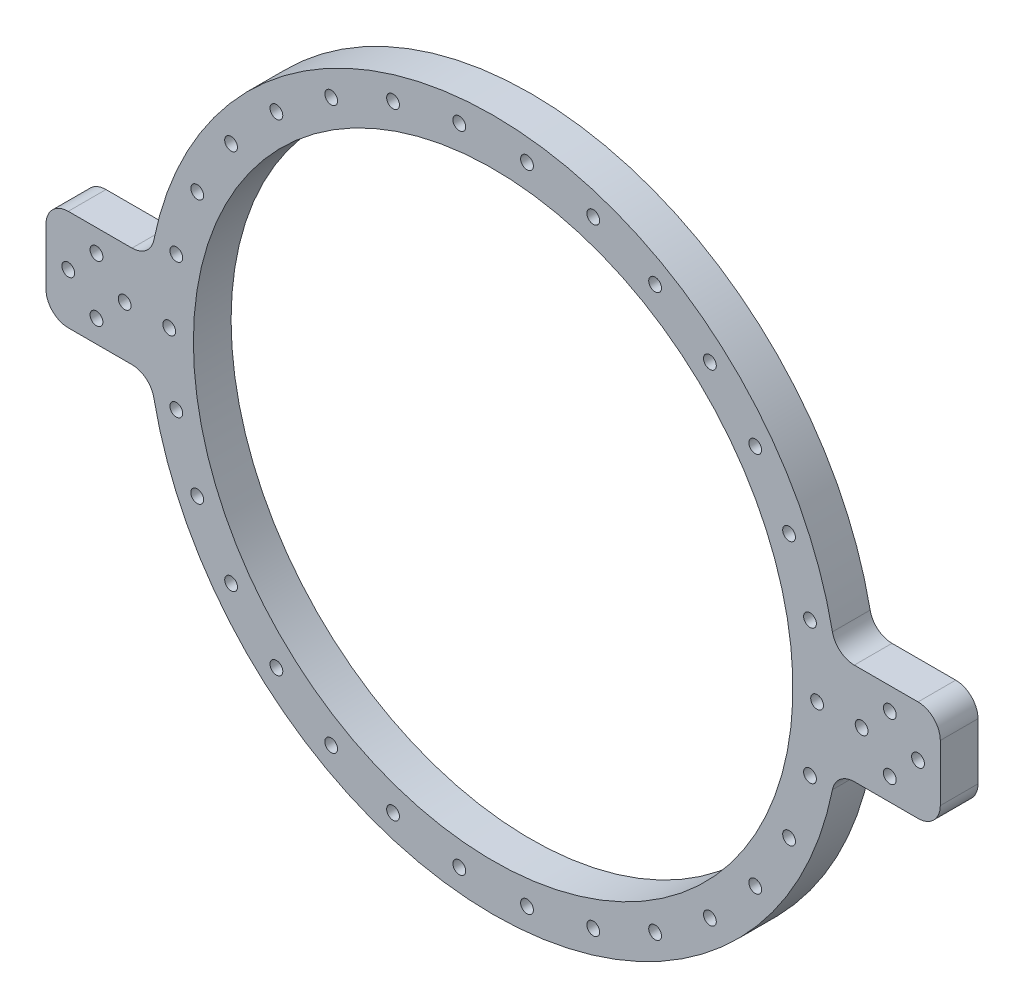
SolidWorks part; units mm, degrees
material "PC High Viscosity"
ref_plane "Front Plane" through (0, 0, 0) normal (0, 0, 1) x (1, 0, 0)
ref_plane "Top Plane" through (0, 0, 0) normal (0, 1, 0) x (1, 0, 0)
ref_plane "Right Plane" through (0, 0, 0) normal (1, 0, 0) x (0, 0, -1)
sketch "Sketch1" plane through (0, 0, 0) normal (0, 0, 1) x (1, 0, 0)
  line L0 (109.1, 0) -> (101.6, 0) construction
  line L1 (109.1, 0) -> (116.6, 0) construction
  line L2 (115.3265, 17) -> (143.1, 17)
  line L3 (150.6, 9.5) -> (150.6, -9.5)
  line L4 (143.1, -17) -> (115.3265, -17)
  line L5 (0, 0) -> (204.7679, 0) construction
  line L6 (0, 0) -> (0, 58.5097) construction
  line L7 (133.6, 9.5) -> (143.1, 0) construction
  line L8 (143.1, 0) -> (133.6, -9.5) construction
  line L9 (133.6, -9.5) -> (124.1, 0) construction
  line L10 (124.1, 0) -> (133.6, 9.5) construction
  line L11 (133.6, 9.5) -> (133.6, 17) construction
  line L12 (124.1, 0) -> (116.6, 0) construction
  line L13 (-115.3265, 17) -> (-143.1, 17)
  line L14 (-150.6, 9.5) -> (-150.6, -9.5)
  line L15 (-143.1, -17) -> (-115.3265, -17)
  circle A0 centre (0, 0) radius 101.6
  arc A1 (115.3265, 17) -> (-115.3265, 17) centre (0, 0) ccw
  circle A2 centre (109.1, 0) radius 2.1527
  circle A4 centre (106.7159, -22.6832) radius 2.1527
  circle A5 centre (99.6678, -44.375) radius 2.1527
  circle A6 centre (88.2638, -64.1274) radius 2.1527
  circle A7 centre (73.0021, -81.0771) radius 2.1527
  circle A8 centre (54.55, -94.4834) radius 2.1527
  circle A9 centre (33.7138, -103.7603) radius 2.1527
  circle A10 centre (11.4041, -108.5023) radius 2.1527
  circle A11 centre (-11.4041, -108.5023) radius 2.1527
  circle A12 centre (-33.7138, -103.7603) radius 2.1527
  circle A13 centre (-54.55, -94.4834) radius 2.1527
  circle A14 centre (-73.0021, -81.0771) radius 2.1527
  circle A15 centre (-88.2638, -64.1274) radius 2.1527
  circle A16 centre (-99.6678, -44.375) radius 2.1527
  circle A17 centre (-106.7159, -22.6832) radius 2.1527
  circle A18 centre (-109.1, 0) radius 2.1527
  circle A19 centre (-106.7159, 22.6832) radius 2.1527
  circle A20 centre (-99.6678, 44.375) radius 2.1527
  circle A21 centre (-88.2638, 64.1274) radius 2.1527
  circle A22 centre (-73.0021, 81.0771) radius 2.1527
  circle A23 centre (-54.55, 94.4834) radius 2.1527
  circle A24 centre (-33.7138, 103.7603) radius 2.1527
  circle A25 centre (-11.4041, 108.5023) radius 2.1526
  circle A26 centre (11.4041, 108.5023) radius 2.1527
  circle A27 centre (33.7138, 103.7603) radius 2.1527
  circle A28 centre (54.55, 94.4834) radius 2.1527
  circle A29 centre (73.0021, 81.0771) radius 2.1527
  circle A30 centre (88.2638, 64.1274) radius 2.1527
  circle A31 centre (99.6678, 44.375) radius 2.1527
  circle A32 centre (106.7159, 22.6832) radius 2.1527
  arc A33 (143.1, 17) -> (150.6, 9.5) centre (143.1, 9.5) cw
  arc A34 (150.6, -9.5) -> (143.1, -17) centre (143.1, -9.5) cw
  circle A35 centre (133.6, 9.5) radius 2.1525
  circle A36 centre (133.6, -9.5) radius 2.1525
  circle A37 centre (143.1, 0) radius 2.1525
  circle A38 centre (124.1, 0) radius 2.1525
  arc A39 (115.3265, -17) -> (116.5727, 0) centre (0, 0) ccw construction
  arc A40 (-143.1, 17) -> (-150.6, 9.5) centre (-143.1, 9.5) ccw
  arc A41 (-150.6, -9.5) -> (-143.1, -17) centre (-143.1, -9.5) ccw
  circle A42 centre (-143.1, 0) radius 2.1525
  circle A43 centre (-133.6, -9.5) radius 2.1525
  circle A44 centre (-124.1, 0) radius 2.1525
  circle A45 centre (-133.6, 9.5) radius 2.1525
  arc A46 (-115.3265, -17) -> (115.3265, -17) centre (0, 0) ccw
  dimension "D1" = 203.2
  dimension "D2" = 30
  dimension "D3" = 4.3053
  dimension "D6" = 19
  dimension "D7" = 4.305
  dimension "D11" = 7.5
  dimension "D13" = 116.5727
  dimension "D14" = 109.1
  dimension "D4" = 7.5
  dimension "D5" = 7.5
  dimension "D8" = 19
  dimension "D9" = 7.5
  dimension "D10" = 7.5
  dimension "D12" = 7.5
  dimension "D15" = 22.8081
extrude "Boss-Extrude1" add sketch "Sketch1" along normal blind 12.7
fillet "Fillet1" radius 7.5 4 edges at (115.3265, -17, 6.35) (115.3265, 17, 6.35) (-115.3265, -17, 6.35) (-115.3265, 17, 6.35)
sketch "Sketch2" plane through (0, 0, 0) normal (0, 0, -1) x (-1, 0, 0)
  circle A0 centre (0, 0) radius 100.965
  circle A1 centre (0, 0) radius 101.6 construction
  circle A2 centre (0, 0) radius 101.6
  dimension "D1" = 201.93
extrude "Boss-Extrude3" add sketch "Sketch2" against normal blind 12.7
